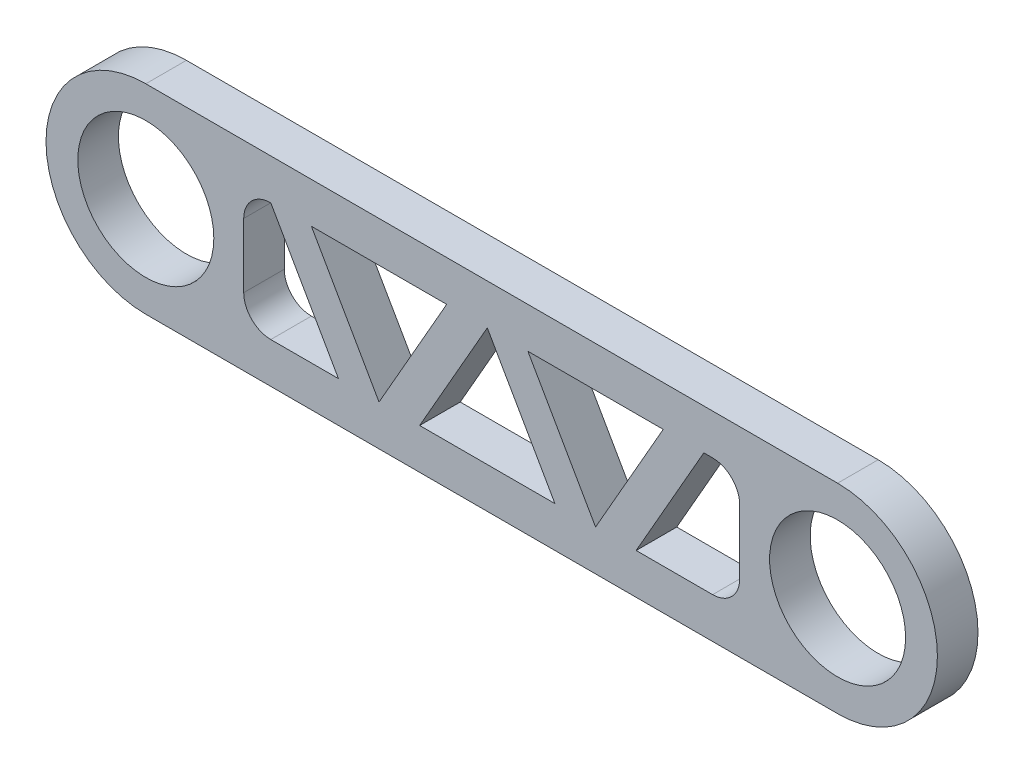
SolidWorks part; units mm, degrees
ref_plane "Front Plane" through (0, 0, 0) normal (0, 0, 1) x (1, 0, 0)
ref_plane "Top Plane" through (0, 0, 0) normal (0, 1, 0) x (1, 0, 0)
ref_plane "Right Plane" through (0, 0, 0) normal (1, 0, 0) x (0, 0, -1)
sketch "Sketch1" plane through (0, 0, 0) normal (0, 0, 1) x (1, 0, 0)
  line L0 (0, 0) -> (204.48, 0) construction
  line L1 (0, 29.5) -> (204.48, 29.5)
  line L2 (0, -29.5) -> (204.48, -29.5)
  arc A0 (0, 29.5) -> (0, -29.5) centre (0, 0) ccw
  arc A1 (204.48, -29.5) -> (204.48, 29.5) centre (204.48, 0) ccw
  point P3 (102.24, 0)
extrude "Boss-Extrude2" add sketch "Sketch1" against normal blind 12 contours L1 A1 L2 A0
sketch "Sketch7" plane through (0, 0, 0) normal (0, 0, 1) x (1, 0, 0)
  line L0 (0, 29.5) -> (204.48, 29.5) construction
  line L1 (36.9389, 17.5) -> (167.5411, 17.5)
  line L2 (28.9389, 9.5) -> (28.9389, -9.5)
  line L3 (36.9389, -17.5) -> (167.5411, -17.5)
  line L4 (175.5411, 9.5) -> (175.5411, -9.5)
  line L5 (0, -29.5) -> (204.48, -29.5) construction
  line L6 (36.9389, 17.5) -> (48.9389, 17.5)
  line L7 (36.9389, 17.5) -> (56.9389, -17.5)
  line L8 (48.9389, 17.5) -> (68.9389, -17.5)
  line L9 (56.9389, -17.5) -> (68.9389, -17.5)
  line L10 (68.9389, -17.5) -> (80.9389, -17.5)
  line L11 (68.9389, -17.5) -> (88.9389, 17.5)
  line L12 (80.9389, -17.5) -> (100.9389, 17.5)
  line L13 (88.9389, 17.5) -> (100.9389, 17.5)
  line L14 (100.9389, 17.5) -> (112.9389, 17.5)
  line L15 (100.9389, 17.5) -> (120.9389, -17.5)
  line L16 (112.9389, 17.5) -> (132.9389, -17.5)
  line L17 (120.9389, -17.5) -> (132.9389, -17.5)
  line L18 (132.9389, -17.5) -> (144.9389, -17.5)
  line L19 (132.9389, -17.5) -> (152.9389, 17.5)
  line L20 (144.9389, -17.5) -> (164.9389, 17.5)
  line L21 (152.9389, 17.5) -> (164.9389, 17.5)
  arc A2 (36.9389, 17.5) -> (28.9389, 9.5) centre (36.9389, 9.5) ccw
  arc A3 (28.9389, -9.5) -> (36.9389, -17.5) centre (36.9389, -9.5) ccw
  arc A4 (167.5411, -17.5) -> (175.5411, -9.5) centre (167.5411, -9.5) ccw
  arc A5 (167.5411, 17.5) -> (175.5411, 9.5) centre (167.5411, 9.5) cw
  point P16 (28.9389, 17.5)
  point P19 (28.9389, -17.5)
  dimension "D5" = 8
  dimension "D1" = 12
  dimension "D2" = 12
  dimension "D6" = 12
  dimension "D7" = 20
  dimension "D8" = 12
  dimension "D9" = 20
  dimension "D10" = 12
  dimension "D11" = 20
  dimension "D12" = 12
  dimension "D13" = 20
extrude "Cut-Extrude4" cut sketch "Sketch7" against normal blind 12 contours L2 A3 L3 L7 A2 | L8 L11 L1 | L15 L12 L3 | L16 L19 L1 | A5 L1 L20 L3 A4 L4
sketch "Sketch8" plane through (0, 0, 0) normal (0, 0, 1) x (1, 0, 0)
  circle A0 centre (0, 0) radius 20.1
extrude "Cut-Extrude5" cut sketch "Sketch8" against normal blind 19 contours A0
sketch "Sketch9" plane through (0, 0, 0) normal (0, 0, 1) x (1, 0, 0)
  circle A0 centre (204.48, 0) radius 20.1
extrude "Cut-Extrude6" cut sketch "Sketch9" against normal blind 19 contours A0
